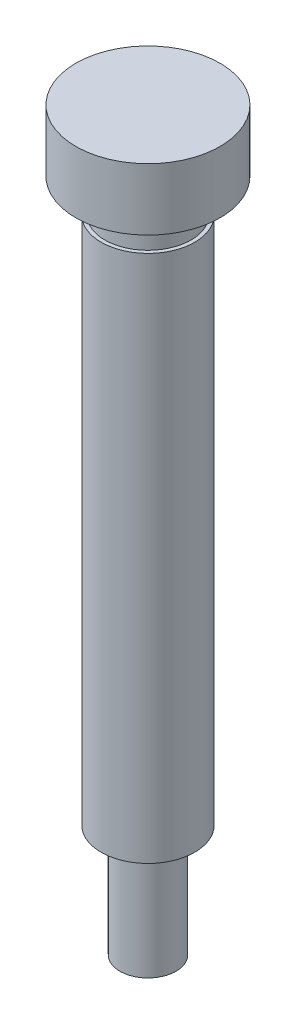
SolidWorks part; units mm, degrees
ref_plane "Front Plane" through (0, 0, 0) normal (0, 0, 1) x (1, 0, 0)
ref_plane "Top Plane" through (0, 0, 0) normal (0, 1, 0) x (1, 0, 0)
ref_plane "Right Plane" through (0, 0, 0) normal (1, 0, 0) x (0, 0, -1)
sketch "Sketch1" plane through (0, 0, 0) normal (0, 0, 1) x (1, 0, 0)
  line L0 (0, 0) -> (1.5, 0)
  line L1 (1.5, 0) -> (1.5, 6)
  line L2 (1.5, 6) -> (2.5, 6)
  line L3 (2.5, 6) -> (2.5, 34.2)
  line L4 (2.3, 34.2) -> (2.3, 36)
  line L5 (2.3, 36) -> (3.85, 36)
  line L6 (3.85, 36) -> (3.85, 39.3)
  line L7 (3.85, 39.3) -> (0, 39.3)
  line L8 (0, 39.3) -> (0, 0)
  line L9 (2.3, 34.2) -> (2.5, 34.2)
  dimension "D1" = 6
  dimension "D2" = 30
  dimension "D3" = 1.8
  dimension "D4" = 1.5
  dimension "D5" = 2.5
  dimension "D6" = 2.3
  dimension "D7" = 3.85
  dimension "D8" = 3.3
revolve "Revolve1" add sketch "Sketch1" angle 360 about L8
